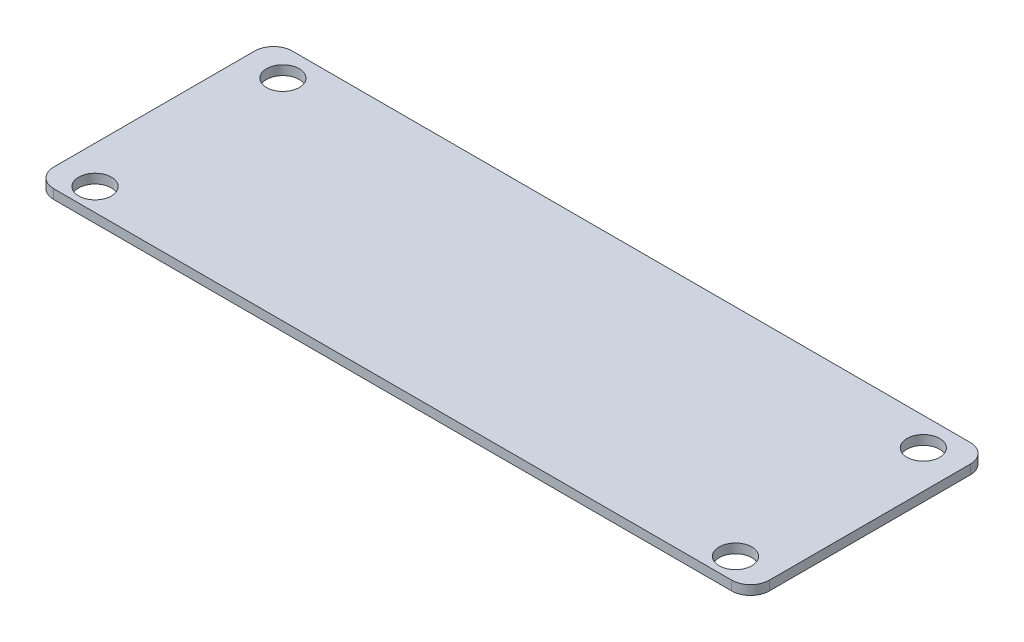
SolidWorks part; units mm, degrees
ref_plane "Front Plane" through (0, 0, 0) normal (0, 0, 1) x (1, 0, 0)
ref_plane "Top Plane" through (0, 0, 0) normal (0, 1, 0) x (1, 0, 0)
ref_plane "Right Plane" through (0, 0, 0) normal (1, 0, 0) x (0, 0, -1)
sketch "Sketch1" plane through (0, 0, 0) normal (0, 1, 0) x (1, 0, 0)
  line L0 (0, 0) -> (0, 8.0468) construction
  line L1 (-36.1, -12.7) -> (36.1, -12.7)
  line L2 (-38.1, -10.7) -> (-38.1, 10.7)
  line L3 (-36.1, 12.7) -> (36.1, 12.7)
  line L4 (38.1, -10.7) -> (38.1, 10.7)
  line L5 (-38.1, -12.7) -> (38.1, 12.7) construction
  line L6 (-38.1, 12.7) -> (38.1, -12.7) construction
  circle A0 centre (-34.1, 9.7) radius 1.7399
  circle A1 centre (-34.1, -10.3) radius 1.7399
  circle A4 centre (34.1, -10.3) radius 1.7399
  circle A5 centre (34.1, 9.7) radius 1.7399
  arc A6 (36.1, 12.7) -> (38.1, 10.7) centre (36.1, 10.7) cw
  arc A7 (36.1, -12.7) -> (38.1, -10.7) centre (36.1, -10.7) ccw
  arc A8 (-36.1, -12.7) -> (-38.1, -10.7) centre (-36.1, -10.7) cw
  arc A9 (-38.1, 10.7) -> (-36.1, 12.7) centre (-36.1, 10.7) cw
  point P0 (0, 0)
  dimension "D3" = 3.4798
  dimension "D4" = 20
  dimension "D5" = 3
  dimension "D6" = 2
  dimension "D7" = 4
  dimension "D1" = 25.4
  dimension "D2" = 76.2
extrude "Boss-Extrude1" add sketch "Sketch1" along normal blind 1 contours L2 A9 L3 A6 L4 A7 L1 A8
